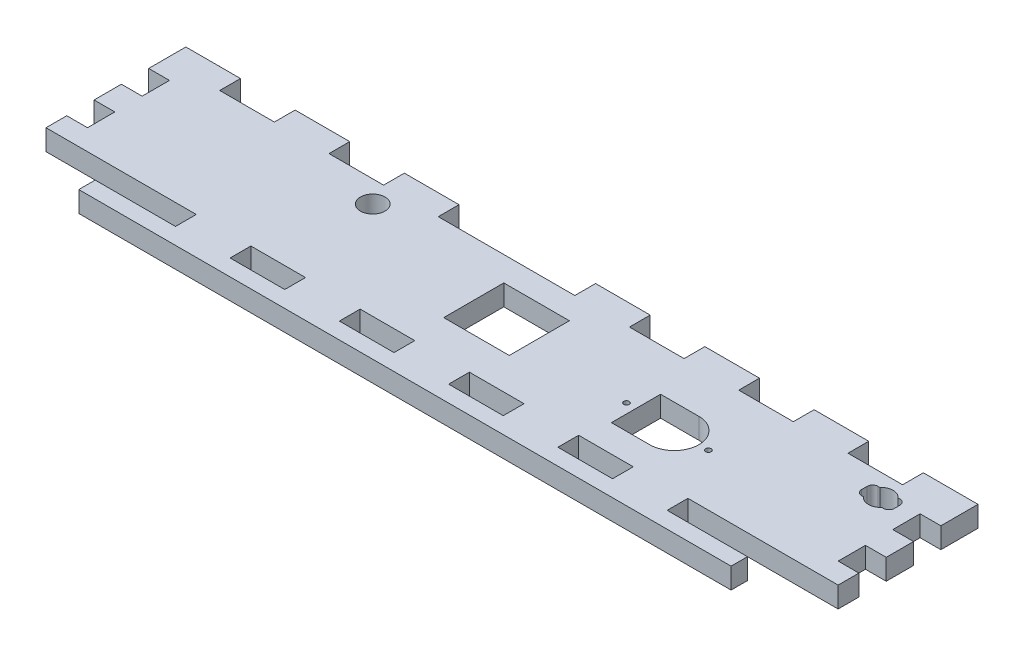
SolidWorks part; units mm, degrees
material "Maple"
ref_plane "Front Plane" through (0, 0, 0) normal (0, 0, 1) x (1, 0, 0)
ref_plane "Top Plane" through (0, 0, 0) normal (0, 1, 0) x (1, 0, 0)
ref_plane "Right Plane" through (0, 0, 0) normal (1, 0, 0) x (0, 0, -1)
sketch "Sketch1" plane through (0, 0, 0) normal (0, 1, 0) x (1, 0, 0)
  line L1 (0, 0) -> (145, 0)
  line L2 (0, 0) -> (0, -21.8)
  line L3 (0, -21.8) -> (145, -21.8)
  line L4 (145, 0) -> (145, -21.8)
  dimension "D1" = 145
  dimension "D2" = 21.8
extrude "Boss-Extrude1" add sketch "Sketch1" along normal blind 3.8
sketch "Sketch2" plane through (0, 3.8, 0) normal (0, 1, 0) x (1, 0, 0)
  line L0 (72.5, -21.8) -> (72.5, 0) construction
  line L1 (0, -21.8) -> (145, -21.8) construction
  line L2 (145, 0) -> (0, 0) construction
  line L4 (66.5, -4.5) -> (78.5, -4.5)
  line L5 (66.5, -4.5) -> (66.5, -15.5)
  line L6 (66.5, -15.5) -> (78.5, -15.5)
  line L7 (78.5, -4.5) -> (78.5, -15.5)
  line L8 (66.5, -4.5) -> (78.5, -15.5) construction
  line L9 (66.5, -15.5) -> (78.5, -4.5) construction
  point P6 (72.5, -10)
  dimension "D1" = 4.5
  dimension "D2" = 11
  dimension "D3" = 12
extrude "Cut-Extrude1" cut sketch "Sketch2" against normal through all
sketch "Sketch3" plane through (0, 3.8, 0) normal (0, 1, 0) x (1, 0, 0)
  line L0 (145, 0) -> (0, 0) construction
  line L1 (0, 0) -> (0, -21.8) construction
  line L3 (145, -21.8) -> (145, 0) construction
  circle A0 centre (42, -4) radius 2.25
  circle A1 centre (135, -4) radius 2.25
  dimension "D1" = 4.5
  dimension "D4" = 4.5
  dimension "D5" = 4
  dimension "D2" = 42
  dimension "D3" = 4
  dimension "D6" = 10
extrude "Cut-Extrude2" cut sketch "Sketch3" against normal through all
sketch "Sketch4" plane through (0, 3.8, 0) normal (0, 1, 0) x (1, 0, 0)
  line L0 (98.5, -12.3) -> (110, -12.3) construction
  line L1 (98.5, -16.8) -> (110, -16.8)
  line L2 (98.5, -16.8) -> (98.5, -7.8)
  line L3 (98.5, -7.8) -> (110, -7.8)
  line L4 (110, -16.8) -> (110, -7.8)
  line L5 (0, -21.8) -> (145, -21.8) construction
  line L6 (145, -21.8) -> (145, 0) construction
  line L7 (104.25, -16.8) -> (104.25, -7.8) construction
  circle A0 centre (105.5, -12.3) radius 4.5
  circle A1 centre (96.75, -12.3) radius 0.5
  circle A2 centre (111.75, -12.3) radius 0.5
  dimension "D5" = 1
  dimension "D6" = 1
  dimension "D1" = 9
  dimension "D2" = 11.5
  dimension "D3" = 5
  dimension "D4" = 35
  dimension "D7" = 15
  dimension "D8" = 7.5
extrude "Cut-Extrude3" cut sketch "Sketch4" against normal through all contours L0 A0 | A0 L3 L2 L1 | A1 | A2
sketch "Sketch5" plane through (0, 3.8, 0) normal (0, 1, 0) x (1, 0, 0)
  line L0 (72.5, 0) -> (72.5, -21.8) construction
  line L1 (145, 0) -> (0, 0) construction
  line L2 (0, -21.8) -> (145, -21.8) construction
  line L4 (67.5, -21.8) -> (77.5, -21.8)
  line L5 (67.5, -21.8) -> (67.5, -25.6)
  line L6 (67.5, -25.6) -> (77.5, -25.6)
  line L7 (77.5, -21.8) -> (77.5, -25.6)
  line L8 (67.5, -21.8) -> (77.5, -25.6) construction
  line L9 (67.5, -25.6) -> (77.5, -21.8) construction
  point P6 (72.5, -23.7)
  dimension "D1" = 3.8
  dimension "D2" = 10
extrude "Boss-Extrude2" add sketch "Sketch5" against normal through all
pattern_linear "LPattern1" count 4 spacing 20 along (-1, 0, 0) count 4 spacing 20 along (1, 0, 0) of "Boss-Extrude2"
sketch "Sketch6" plane through (0, 3.8, 0) normal (0, 1, 0) x (1, 0, 0)
  line L0 (7.5, -25.6) -> (17.5, -25.6) construction
  line L1 (0, -25.6) -> (145, -25.6)
  line L2 (0, -25.6) -> (0, -28.6)
  line L3 (0, -28.6) -> (145, -28.6)
  line L4 (145, -25.6) -> (145, -28.6)
  line L5 (0, 0) -> (0, -21.8) construction
  line L6 (145, -21.8) -> (145, 0) construction
  dimension "D1" = 3
extrude "Boss-Extrude3" add sketch "Sketch6" against normal through all
sketch "Sketch8" plane through (0, 0, 0) normal (0, -1, 0) x (-1, 0, 0)
  line L1 (-7.5, -25.6) -> (-17.5, -25.6)
  line L2 (-7.5, -25.6) -> (-7.5, -21.8)
  line L3 (-7.5, -21.8) -> (-17.5, -21.8)
  line L4 (-17.5, -25.6) -> (-17.5, -21.8)
  line L5 (-137.5, -25.6) -> (-127.5, -25.6)
  line L6 (-137.5, -25.6) -> (-137.5, -21.8)
  line L7 (-137.5, -21.8) -> (-127.5, -21.8)
  line L8 (-127.5, -25.6) -> (-127.5, -21.8)
extrude "Cut-Extrude4" cut sketch "Sketch8" against normal through all
sketch "Sketch9" plane through (0, 3.8, 0) normal (0, 1, 0) x (1, 0, 0)
  line L0 (0, 0) -> (0, -21.8) construction
  line L1 (3.8, -13) -> (0, -13)
  line L2 (3.8, -13) -> (3.8, -18)
  line L3 (3.8, -18) -> (0, -18)
  line L4 (0, -13) -> (0, -18)
  line L5 (0, 0) -> (0, -21.8) construction
  line L6 (145, -21.8) -> (145, 0) construction
  line L7 (3.8, -3) -> (0, -3)
  line L8 (3.8, -3) -> (3.8, -8)
  line L9 (3.8, -8) -> (0, -8)
  line L10 (0, -3) -> (0, -8)
  line L11 (141.2, -13) -> (145, -13)
  line L12 (141.2, -13) -> (141.2, -18)
  line L13 (141.2, -18) -> (145, -18)
  line L14 (145, -13) -> (145, -18)
  line L15 (145, 0) -> (0, 0) construction
  line L16 (141.2, -3) -> (145, -3)
  line L17 (141.2, -3) -> (141.2, -8)
  line L18 (141.2, -8) -> (145, -8)
  line L19 (145, -3) -> (145, -8)
  dimension "D1" = 3
  dimension "D2" = 5
  dimension "D3" = 5
  dimension "D4" = 5
  dimension "D5" = 3.8
extrude "Cut-Extrude5" cut sketch "Sketch9" against normal through all
sketch "Sketch10" plane through (0, 0, 0) normal (0, -1, 0) x (-1, 0, 0)
  line L0 (-27.5, -25.6) -> (0, -25.6) construction
  line L1 (0, -28.6) -> (-12.8, -28.6)
  line L2 (0, -28.6) -> (0, -25.6)
  line L3 (0, -25.6) -> (-12.8, -25.6)
  line L4 (-12.8, -28.6) -> (-12.8, -25.6)
  line L5 (-145, -25.6) -> (-117.5, -25.6) construction
  line L6 (-145, -28.6) -> (-132.2, -28.6)
  line L7 (-145, -28.6) -> (-145, -25.6)
  line L8 (-145, -25.6) -> (-132.2, -25.6)
  line L9 (-132.2, -28.6) -> (-132.2, -25.6)
  dimension "D1" = 12.8
extrude "Cut-Extrude6" cut sketch "Sketch10" against normal through all
sketch "Sketch11" plane through (0, 0, 0) normal (0, -1, 0) x (-1, 0, 0)
  line L1 (0, 0) -> (-10, 0)
  line L2 (0, 0) -> (0, 3.8)
  line L3 (0, 3.8) -> (-10, 3.8)
  line L4 (-10, 0) -> (-10, 3.8)
  dimension "D1" = 10
  dimension "D2" = 3.8
extrude "Boss-Extrude4" add sketch "Sketch11" against normal through all
pattern_linear "LPattern2" count 3 spacing 20 along (1, 0, 0) of "Boss-Extrude4"
sketch "Sketch12" plane through (0, 0, 0) normal (0, -1, 0) x (-1, 0, 0)
  line L1 (-145, 0) -> (-135, 0)
  line L2 (-145, 0) -> (-145, 3.8)
  line L3 (-145, 3.8) -> (-135, 3.8)
  line L4 (-135, 0) -> (-135, 3.8)
  dimension "D1" = 3.8
  dimension "D2" = 10
extrude "Boss-Extrude5" add sketch "Sketch12" against normal through all
pattern_linear "LPattern3" count 4 spacing 20 along (-1, 0, 0) of "Boss-Extrude5"
sketch "Sketch13" plane through (0, 3.8, 0) normal (0, 1, 0) x (1, 0, 0)
  line L0 (132.75, -4) -> (137.25, -4) construction
  line L1 (135, -1.75) -> (135, -6.25) construction
  line L2 (132, -2.5) -> (138, -2.5)
  line L3 (132, -2.5) -> (132, -5.5)
  line L4 (132, -5.5) -> (138, -5.5)
  line L5 (138, -2.5) -> (138, -5.5)
  line L6 (132, -2.5) -> (138, -5.5) construction
  line L7 (132, -5.5) -> (138, -2.5) construction
  circle A0 centre (135, -4) radius 2.25 construction
  point P4 (135, -4)
  dimension "D1" = 3
  dimension "D2" = 6
extrude "Cut-Extrude7" cut sketch "Sketch13" against normal through all
fillet "Fillet1" radius 1 4 edges at (138, 1.9, 5.5) (138, 1.9, 2.5) (132, 1.9, 5.5) (132, 1.9, 2.5)
equation "\"D6@Sketch4\"=\"D5@Sketch4\""
equation "\"D8@Sketch4\"=\"D7@Sketch4\"/2"
